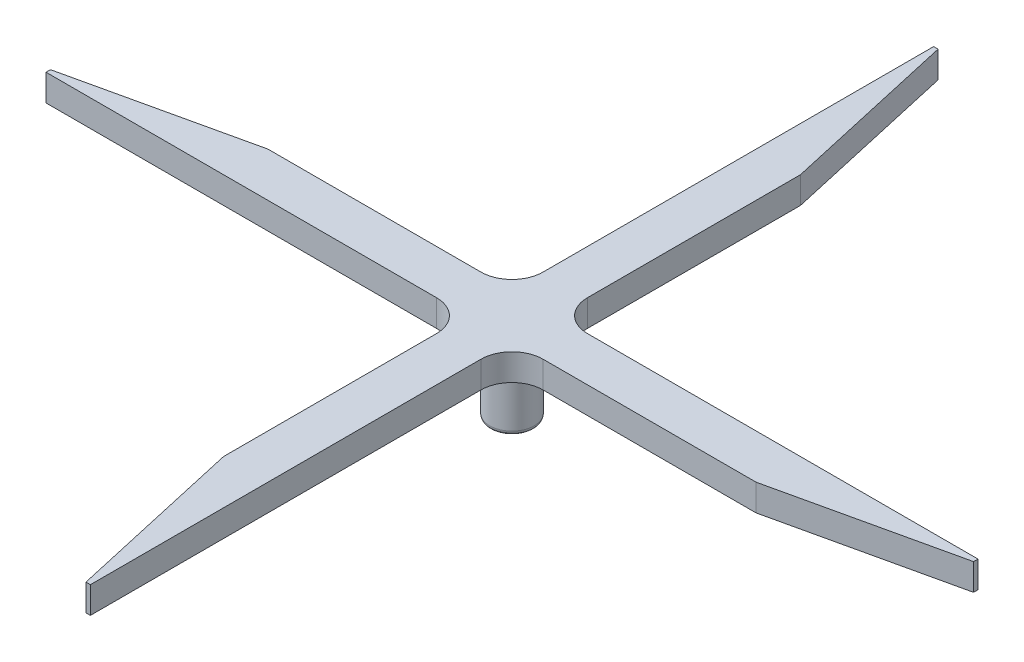
SolidWorks part; units mm, degrees
ref_plane "Front Plane" through (0, 0, 0) normal (0, 0, 1) x (1, 0, 0)
ref_plane "Top Plane" through (0, 0, 0) normal (0, 1, 0) x (1, 0, 0)
ref_plane "Right Plane" through (0, 0, 0) normal (1, 0, 0) x (0, 0, -1)
sketch "Sketch1" plane through (0, 0, 0) normal (0, 1, 0) x (1, 0, 0)
  line L0 (15.24, 6.35) -> (127, 6.35)
  line L1 (-127, 6.35) -> (-15.24, 6.35)
  line L2 (-127, 6.35) -> (-127, -6.35)
  line L3 (-127, -6.35) -> (-15.24, -6.35)
  line L4 (127, 6.35) -> (127, -6.35)
  line L5 (-6.35, 127) -> (6.35, 127)
  line L6 (-6.35, 127) -> (-6.35, 15.24)
  line L7 (-6.35, -127) -> (6.35, -127)
  line L8 (6.35, 127) -> (6.35, 15.24)
  line L9 (6.35, -15.24) -> (6.35, -127)
  line L10 (15.24, -6.35) -> (127, -6.35)
  line L11 (-6.35, -15.24) -> (-6.35, -127)
  arc A0 (-15.24, -6.35) -> (-6.35, -15.24) centre (-15.24, -15.24) cw
  arc A1 (6.35, -15.24) -> (15.24, -6.35) centre (15.24, -15.24) cw
  arc A2 (15.24, 6.35) -> (6.35, 15.24) centre (15.24, 15.24) cw
  arc A3 (-15.24, 6.35) -> (-6.35, 15.24) centre (-15.24, 15.24) ccw
  point P15 (-6.35, -6.35)
  point P18 (6.35, -6.35)
  dimension "D9" = 8.89
  dimension "D1" = 6.35
  dimension "D2" = 12.7
  dimension "D3" = 127
  dimension "D4" = 254
  dimension "D5" = 6.35
  dimension "D6" = 12.7
  dimension "D7" = 127
  dimension "D8" = 254
extrude "Boss-Extrude1" add sketch "Sketch1" along normal blind 7.62
sketch "Sketch2" plane through (0, 7.62, 0) normal (0, 1, 0) x (1, 0, 0)
  line L0 (127, 5.08) -> (76.2, -6.35)
  line L1 (6.35, 127) -> (-6.35, 127) construction
  line L2 (-5.08, 127) -> (6.35, 76.2)
  line L3 (6.35, 15.24) -> (6.35, 127) construction
  line L4 (6.35, 76.2) -> (6.35, 127)
  line L5 (6.35, 127) -> (-5.08, 127)
  line L6 (76.2, -6.35) -> (127, -6.35)
  line L7 (127, -6.35) -> (127, 5.08)
  line L8 (5.08, -127) -> (-6.35, -76.2)
  line L9 (-6.35, -76.2) -> (-6.35, -127)
  line L10 (-6.35, -127) -> (5.08, -127)
  line L11 (-127, -5.08) -> (-76.2, 6.35)
  line L12 (-76.2, 6.35) -> (-127, 6.35)
  line L13 (-127, 6.35) -> (-127, -5.08)
  dimension "D1" = 11.43
  dimension "D2" = 50.8
  dimension "D3" = 4
extrude "Cut-Extrude1" cut sketch "Sketch2" against normal through all
sketch "Sketch3" plane through (0, 7.62, 0) normal (0, 1, 0) x (1, 0, 0)
  circle A0 centre (0, 0) radius 6.35
  dimension "D1" = 12.7
extrude "Boss-Extrude2" add sketch "Sketch3" against normal blind 25.4
fillet "Fillet1" radius 1.27 1 edges at (0, 0, -6.35)
fillet "Fillet2" radius 1.27 1 edges at (0, -17.78, 6.35)
